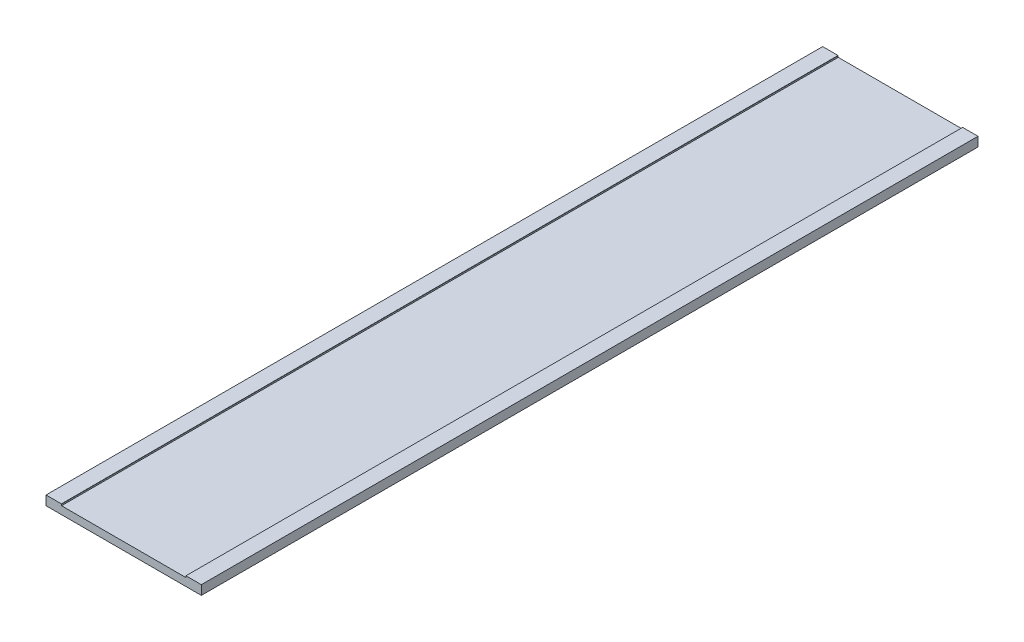
SolidWorks part; units mm, degrees
ref_plane "Plan de face" through (0, 0, 0) normal (0, 0, 1) x (1, 0, 0)
ref_plane "Plan de dessus" through (0, 0, 0) normal (0, 1, 0) x (1, 0, 0)
ref_plane "Plan de droite" through (0, 0, 0) normal (1, 0, 0) x (0, 0, -1)
sketch "Esquisse1" plane through (0, 0, 0) normal (0, 0, 1) x (1, 0, 0)
  line L0 (-13233.7386, 0) -> (16709.7642, 0) construction
  line L1 (-10098.1454, 0) -> (-10098.1454, 1200)
  line L2 (-10098.1454, 1200) -> (-8098.1454, 1200)
  line L3 (-8098.1454, 1200) -> (-8098.1454, 1000)
  line L4 (-8098.1454, 1000) -> (0, 1000)
  line L5 (0, 1000) -> (7901.8546, 1000)
  line L6 (7901.8546, 1000) -> (7901.8546, 1200)
  line L7 (7901.8546, 1200) -> (9901.8546, 1200)
  line L8 (9901.8546, 1200) -> (9901.8546, 0)
  line L9 (9901.8546, 0) -> (-10098.1454, 0)
  dimension "D1" = 20000
  dimension "D2" = 1000
  dimension "D3" = 1200
  dimension "D4" = 1200
  dimension "D5" = 2000
  dimension "D6" = 2000
extrude "Boss.-Extru.1" add sketch "Esquisse1" along normal blind 100000
chamfer "Chanfrein1" distance 20 angle 45 1 edges at (-8098.1454, 1200, 50000)
chamfer "Chanfrein2" distance 20 angle 45 1 edges at (7901.8546, 1200, 50000)
